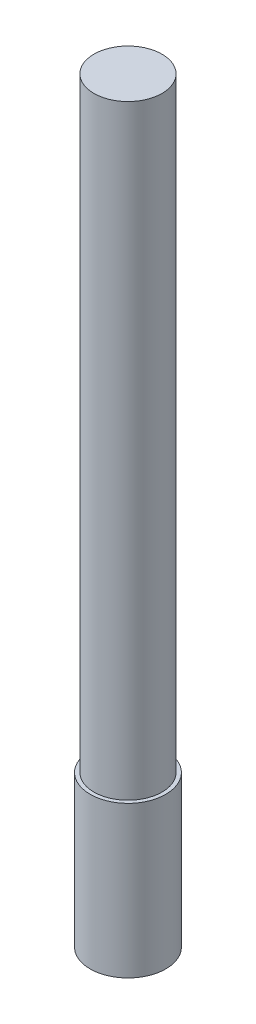
SolidWorks part; units mm, degrees
ref_plane "Front Plane" through (0, 0, 0) normal (0, 0, 1) x (1, 0, 0)
ref_plane "Top Plane" through (0, 0, 0) normal (0, 1, 0) x (1, 0, 0)
ref_plane "Right Plane" through (0, 0, 0) normal (1, 0, 0) x (0, 0, -1)
sketch "Sketch1" plane through (0, 0, 0) normal (0, 1, 0) x (1, 0, 0)
  circle A0 centre (0, 0) radius 2.5
  dimension "D1" = 5
extrude "Boss-Extrude1" add sketch "Sketch1" along normal mid plane 10
sketch "Sketch2" plane through (0, 5, 0) normal (0, 1, 0) x (1, 0, 0)
  circle A0 centre (0, 0) radius 2.25
  dimension "D1" = 4.5
extrude "Boss-Extrude2" add sketch "Sketch2" along normal blind 40
